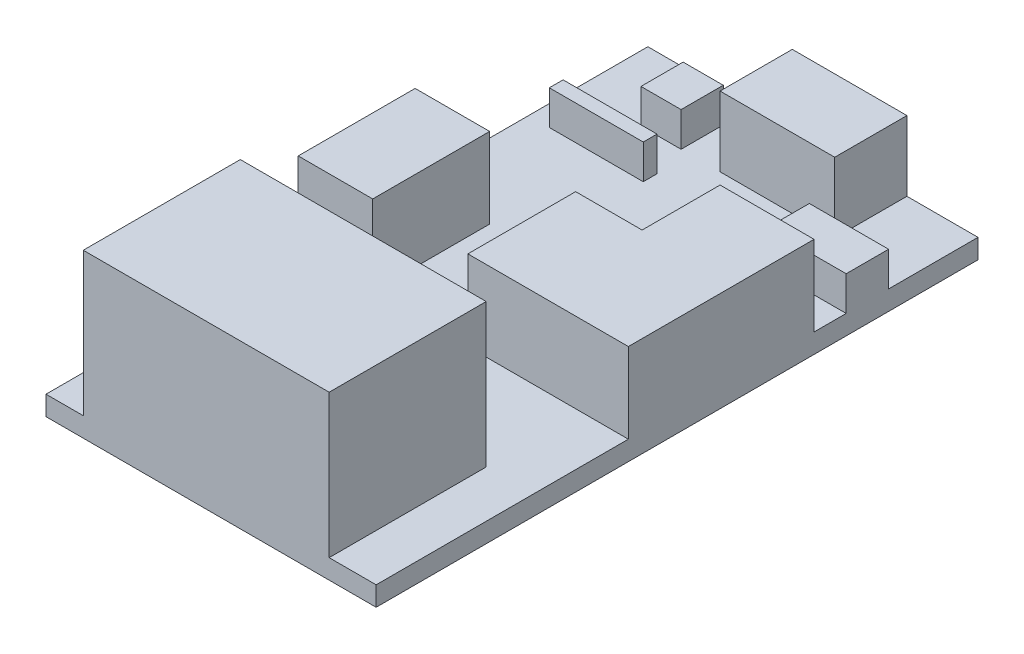
SolidWorks part; units mm, degrees
ref_plane "Front" through (0, 0, 0) normal (0, 0, 1) x (1, 0, 0)
ref_plane "Top" through (0, 0, 0) normal (0, 1, 0) x (1, 0, 0)
ref_plane "Right" through (0, 0, 0) normal (1, 0, 0) x (0, 0, -1)
sketch "Szkic1" plane through (0, 0, 0) normal (0, 1, 0) x (1, 0, 0)
  line L1 (-18.5714, 22.4603) -> (10.2286, 22.4603)
  line L2 (-18.5714, 22.4603) -> (-18.5714, -30.0397)
  line L3 (-18.5714, -30.0397) -> (10.2286, -30.0397)
  line L4 (10.2286, 22.4603) -> (10.2286, -30.0397)
  dimension "D1" = 28.8
  dimension "D2" = 52.5
extrude "Dodanie-wyciągnięcie1" add sketch "Szkic1" along normal blind 1.7
sketch "Szkic2" plane through (0, 1.7, 0) normal (0, 1, 0) x (1, 0, 0)
  line L0 (6.1286, -30.0397) -> (6.1286, 37.8487) construction
  line L1 (-18.5714, -30.0397) -> (10.2286, -30.0397) construction
  line L2 (10.2286, -30.0397) -> (10.2286, 22.4603) construction
  line L3 (-15.3214, -30.0397) -> (-15.3214, 33.7739) construction
  line L4 (-18.5714, 22.4603) -> (-18.5714, -30.0397) construction
  line L5 (-23.6897, -16.3397) -> (37.3463, -16.3397) construction
  line L7 (-15.3214, -30.0397) -> (6.1286, -30.0397)
  line L8 (-15.3214, -30.0397) -> (-15.3214, -16.3397)
  line L9 (-15.3214, -16.3397) -> (6.1286, -16.3397)
  line L10 (6.1286, -30.0397) -> (6.1286, -16.3397)
  dimension "D1" = 4.1
  dimension "D2" = 3.25
  dimension "D3" = 13.7
extrude "Dodanie-wyciągnięcie2" add sketch "Szkic2" along normal blind 12.5
sketch "Szkic3" plane through (0, 1.7, 0) normal (0, 1, 0) x (1, 0, 0)
  line L0 (4.0286, 22.4603) -> (4.0286, -1.492) construction
  line L1 (10.2286, 22.4603) -> (-18.5714, 22.4603) construction
  line L2 (10.2286, -30.0397) -> (10.2286, 22.4603) construction
  line L3 (-5.9714, 0) -> (-5.9714, 41.0944) construction
  line L4 (17.641, 16.1603) -> (-23.8756, 16.1603) construction
  line L6 (-5.9714, 22.4603) -> (4.0286, 22.4603)
  line L7 (-5.9714, 22.4603) -> (-5.9714, 16.1603)
  line L8 (-5.9714, 16.1603) -> (4.0286, 16.1603)
  line L9 (4.0286, 22.4603) -> (4.0286, 16.1603)
  dimension "D1" = 6.2
  dimension "D2" = 16.2
  dimension "D3" = 6.3
extrude "Dodanie-wyciągnięcie3" add sketch "Szkic3" along normal blind 6.1
sketch "Szkic4" plane through (0, 1.7, 0) normal (0, 1, 0) x (1, 0, 0)
  line L0 (10.2286, 14.6603) -> (-35.2099, 14.6603) construction
  line L1 (10.2286, -30.0397) -> (10.2286, 22.4603) construction
  line L2 (10.2286, 22.4603) -> (4.0286, 22.4603) construction
  line L3 (10.2286, 10.9603) -> (-36.6918, 10.9603) construction
  line L5 (10.2286, 10.9603) -> (3.3156, 10.9603)
  line L6 (10.2286, 10.9603) -> (10.2286, 14.6603)
  line L7 (10.2286, 14.6603) -> (3.3156, 14.6603)
  line L8 (3.3156, 10.9603) -> (3.3156, 14.6603)
  dimension "D1" = 7.8
  dimension "D2" = 11.5
extrude "Dodanie-wyciągnięcie4" add sketch "Szkic4" along normal blind 3
sketch "Szkic5" plane through (0, 0, 0) normal (0, -1, 0) x (1, 0, 0)
  circle A0 centre (-5.4277, 24.8745) radius 1.4514
  circle A1 centre (0, 21.3861) radius 1.0167
  circle A2 centre (-6.8791, -3.1625) radius 1.9908
  circle A3 centre (-1.0167, -10.6892) radius 0.7098
extrude "Dodanie-wyciągnięcie5" add sketch "Szkic5" along normal blind 2.5
sketch "Szkic6" plane through (0, 1.7, 0) normal (0, 1, 0) x (1, 0, 0)
  line L0 (-5.9714, 16.1603) -> (-32.6409, 16.1603) construction
  line L1 (-12.8714, 16.1603) -> (-12.8714, 33.1172) construction
  line L2 (-18.5714, 22.4603) -> (-18.5714, -30.0397) construction
  line L3 (-9.3714, 16.1603) -> (-9.3714, 34.5615) construction
  line L5 (-9.3714, 16.1603) -> (-12.8714, 16.1603)
  line L6 (-9.3714, 16.1603) -> (-9.3714, 19.8387)
  line L7 (-9.3714, 19.8387) -> (-12.8714, 19.8387)
  line L8 (-12.8714, 16.1603) -> (-12.8714, 19.8387)
  dimension "D1" = 5.7
  dimension "D2" = 9.2
extrude "Dodanie-wyciągnięcie6" add sketch "Szkic6" along normal up to surface (3 mm away) up to face at (6.7721, 4.7, -12.8103)
sketch "Szkic7" plane through (0, 1.7, 0) normal (0, 1, 0) x (1, 0, 0)
  line L0 (-18.5714, 13.2603) -> (29.8709, 13.2603) construction
  line L1 (-18.5714, 22.4603) -> (-18.5714, -30.0397) construction
  line L2 (-5.9714, 22.4603) -> (-18.5714, 22.4603) construction
  line L3 (-18.5714, 12.0603) -> (22.2995, 12.0603) construction
  line L4 (-8.5714, 12.0603) -> (-8.5714, 28.5497) construction
  line L6 (-8.5714, 12.0603) -> (-16.7653, 12.0603)
  line L7 (-8.5714, 12.0603) -> (-8.5714, 13.2603)
  line L8 (-8.5714, 13.2603) -> (-16.7653, 13.2603)
  line L9 (-16.7653, 12.0603) -> (-16.7653, 13.2603)
  dimension "D1" = 9.2
  dimension "D2" = 10.4
  dimension "D3" = 10
extrude "Dodanie-wyciągnięcie7" add sketch "Szkic7" along normal up to surface (3 mm away) up to face at (6.7721, 4.7, -12.8103)
sketch "Szkic8" plane through (0, 1.7, 0) normal (0, 1, 0) x (1, 0, 0)
  line L0 (-18.5714, -8.0397) -> (26.7191, -8.0397) construction
  line L1 (-18.5714, 22.4603) -> (-18.5714, -30.0397) construction
  line L2 (-5.9714, 22.4603) -> (-18.5714, 22.4603) construction
  line L3 (-18.5714, 2.1603) -> (28.9929, 2.1603) construction
  line L4 (-12.0714, 30.0032) -> (-12.0714, -8.0397) construction
  line L5 (-3.7714, -8.0397) -> (-3.7714, 36.1375) construction
  line L6 (-18.5714, 2.1603) -> (-12.0714, 2.1603)
  line L7 (-18.5714, 2.1603) -> (-18.5714, -8.0397)
  line L8 (-18.5714, -8.0397) -> (-12.0714, -8.0397)
  line L9 (-12.0714, 2.1603) -> (-12.0714, -8.0397)
  line L10 (10.2286, -30.0397) -> (10.2286, 10.9603) construction
  line L11 (10.2286, -8.0397) -> (-3.7714, -8.0397)
  line L12 (-3.7714, -8.0397) -> (-3.7714, 1.3603)
  line L13 (2.0286, 2.1603) -> (2.0286, 29.2805) construction
  line L14 (-3.7714, 1.3603) -> (2.0286, 1.3603)
  line L15 (2.0286, 1.3603) -> (2.0286, 8.1603)
  line L16 (2.0286, 8.1603) -> (10.2286, 8.1603)
  line L17 (10.2286, 8.1603) -> (10.2286, -8.0397)
  dimension "D1" = 30.5
  dimension "D2" = 20.3
  dimension "D3" = 6.5
  dimension "D4" = 14
  dimension "D5" = 9.4
  dimension "D6" = 8.2
  dimension "D7" = 6.8
extrude "Dodanie-wyciągnięcie8" add sketch "Szkic8" along normal blind 7
